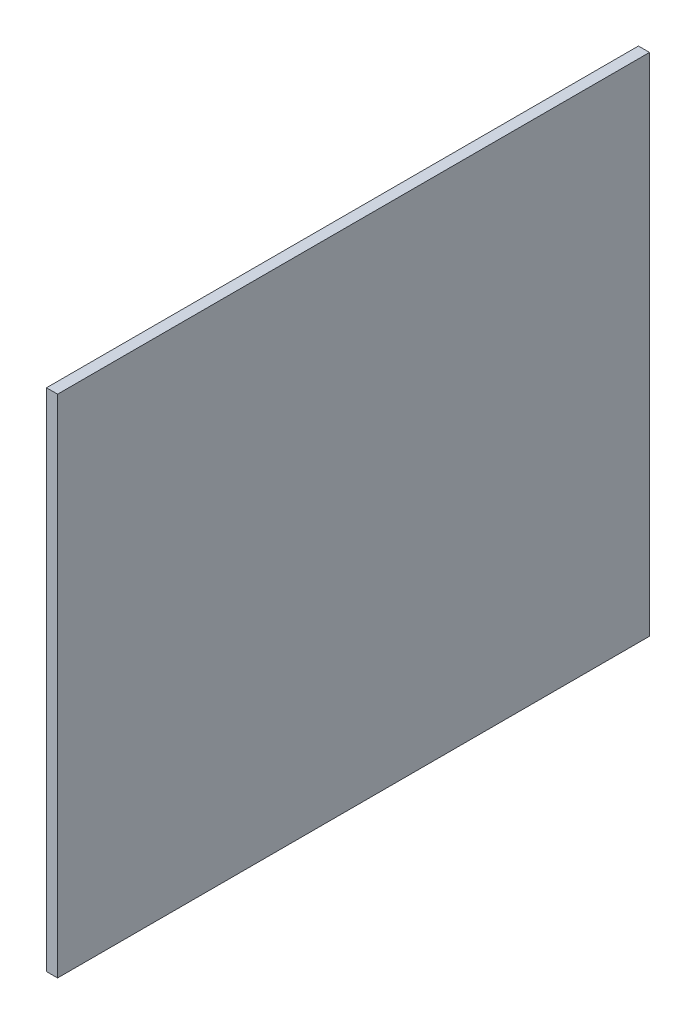
SolidWorks part; units mm, degrees
material "Pine"
ref_plane "Front Plane" through (0, 0, 0) normal (0, 0, 1) x (1, 0, 0)
ref_plane "Top Plane" through (0, 0, 0) normal (0, 1, 0) x (1, 0, 0)
ref_plane "Right Plane" through (0, 0, 0) normal (1, 0, 0) x (0, 0, -1)
sketch "Sketch1" plane through (0, 0, 0) normal (1, 0, 0) x (0, 0, -1)
  line L1 (-480, 410) -> (480, 410)
  line L2 (-480, 410) -> (-480, -410)
  line L3 (-480, -410) -> (480, -410)
  line L4 (480, 410) -> (480, -410)
  line L5 (-480, 410) -> (480, -410) construction
  line L6 (-480, -410) -> (480, 410) construction
  point P0 (0, 0)
  dimension "D1" = 820
  dimension "D2" = 960
extrude "Boss-Extrude1" add sketch "Sketch1" along normal blind 18
